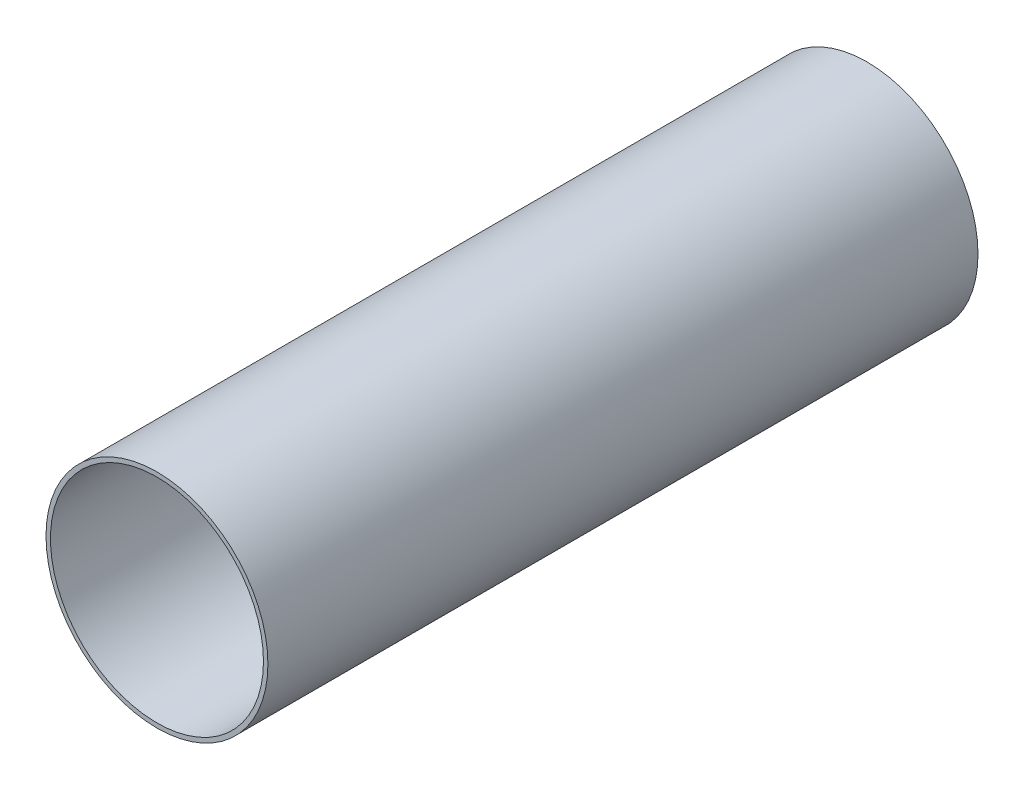
SolidWorks part; units mm, degrees
ref_plane "Plan de face" through (0, 0, 0) normal (0, 0, 1) x (1, 0, 0)
ref_plane "Plan de dessus" through (0, 0, 0) normal (0, 1, 0) x (1, 0, 0)
ref_plane "Plan de droite" through (0, 0, 0) normal (1, 0, 0) x (0, 0, -1)
sketch "Esquisse1" plane through (0, 0, 0) normal (0, 0, 1) x (1, 0, 0)
  circle A0 centre (0, 0) radius 25
  circle A1 centre (0, 0) radius 24
  dimension "D1" = 50
  dimension "D2" = 1
extrude "Boss.-Extru.1" add sketch "Esquisse1" along normal blind 160
